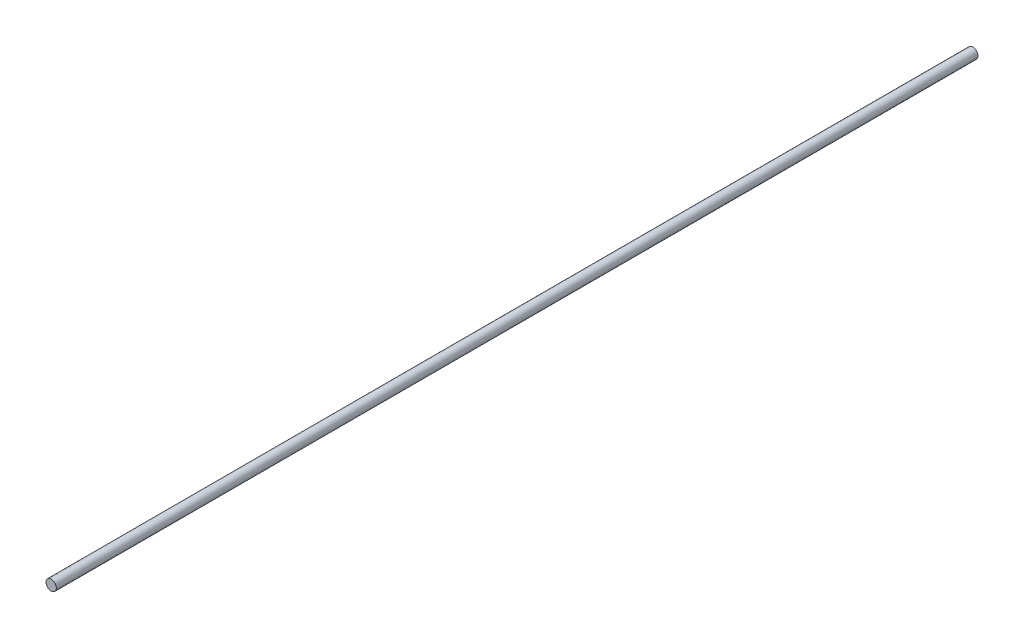
SolidWorks part; units mm, degrees
ref_plane "Front Plane" through (0, 0, 0) normal (0, 0, 1) x (1, 0, 0)
ref_plane "Top Plane" through (0, 0, 0) normal (0, 1, 0) x (1, 0, 0)
ref_plane "Right Plane" through (0, 0, 0) normal (1, 0, 0) x (0, 0, -1)
sketch "Sketch1" plane through (0, 0, 0) normal (0, 0, 1) x (1, 0, 0)
  circle A0 centre (0, 0) radius 4.5
extrude "Boss-Extrude1" add sketch "Sketch1" along normal mid plane 800
